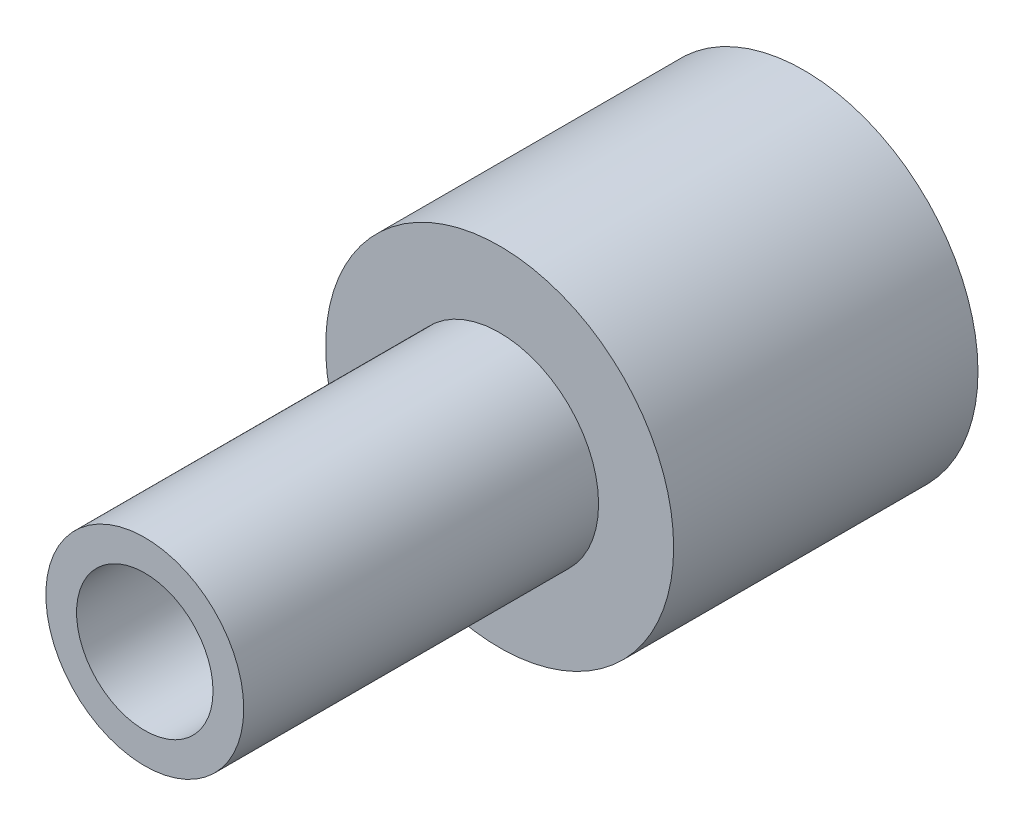
SolidWorks part; units mm, degrees
material "Polyetheretherketone (PEEK)"
ref_plane "Front Plane" through (0, 0, 0) normal (0, 0, 1) x (1, 0, 0)
ref_plane "Top Plane" through (0, 0, 0) normal (0, 1, 0) x (1, 0, 0)
ref_plane "Right Plane" through (0, 0, 0) normal (1, 0, 0) x (0, 0, -1)
sketch "Sketch1" plane through (0, 0, 0) normal (0, 0, 1) x (1, 0, 0)
  circle A0 centre (0, 0) radius 0.6477
  circle A1 centre (0, 0) radius 0.254
extrude "Extrude1" add sketch "Sketch1" against normal blind 1.1328
sketch "Sketch2" plane through (0, 0, 0) normal (0, 0, 1) x (1, 0, 0)
  circle A0 centre (0, 0) radius 0.3683
extrude "Extrude2" add sketch "Sketch2" along normal blind 1.3208
sketch "Sketch4" plane through (0, 0, 0) normal (0, 0, -1) x (-1, 0, 0)
  circle A0 centre (0, 0) radius 0.254
extrude "Cut-Extrude1" cut sketch "Sketch4" against normal up to next
